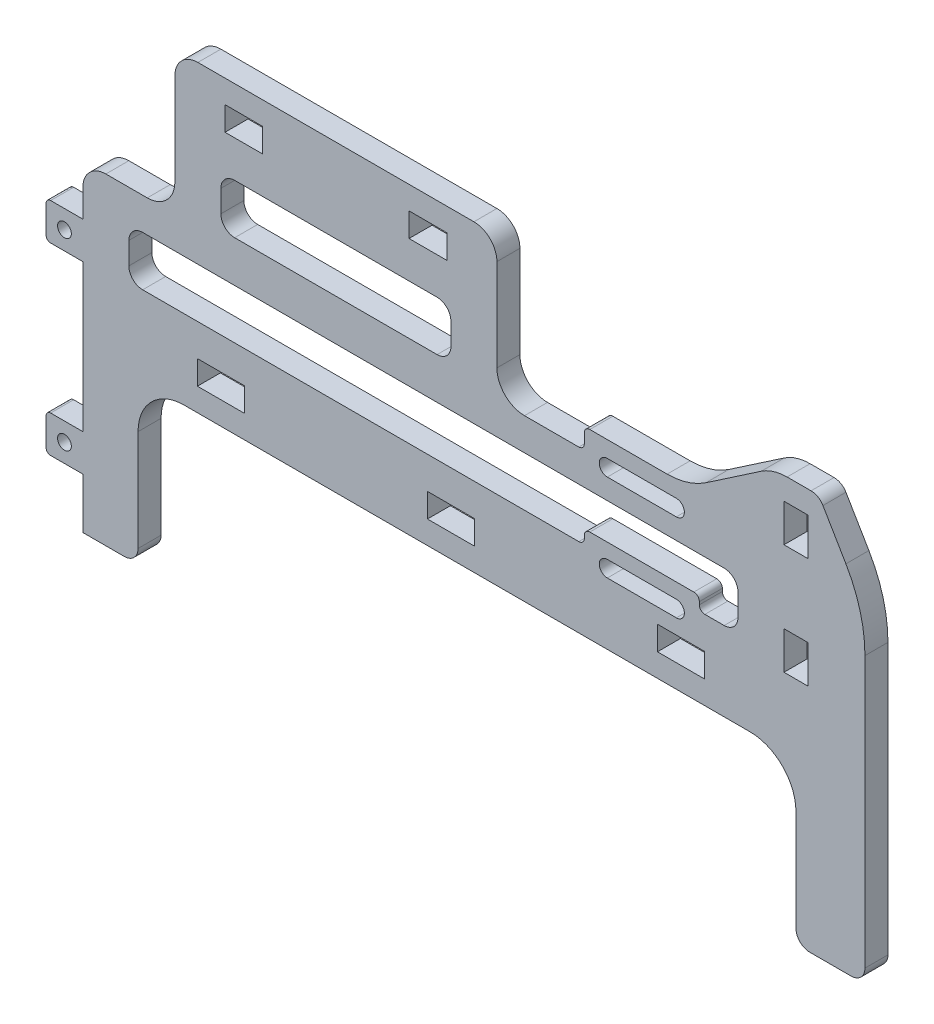
SolidWorks part; units mm, degrees
ref_plane "Alzado" through (0, 0, 0) normal (0, 0, 1) x (1, 0, 0)
ref_plane "Planta" through (0, 0, 0) normal (0, 1, 0) x (1, 0, 0)
ref_plane "Vista lateral" through (0, 0, 0) normal (1, 0, 0) x (0, 0, -1)
sketch "Croquis1" plane through (0, 0, 0) normal (0, 0, 1) x (1, 0, 0)
  line L0 (0, 0) -> (0, 70)
  line L1 (0, 70) -> (125, 70)
  line L2 (125, 70) -> (150, 87)
  line L3 (150, 87) -> (160, 87)
  line L4 (160, 87) -> (170, 70)
  line L5 (170, 70) -> (170, 0)
  line L6 (170, 0) -> (0, 0)
  dimension "D1" = 17
  dimension "D2" = 70
  dimension "D3" = 125
  dimension "D4" = 10
  dimension "D5" = 10
  dimension "D6" = 25
extrude "Saliente-Extruir1" add sketch "Croquis1" along normal blind 5
sketch "Croquis2" plane through (0, 0, 5) normal (0, 0, 1) x (1, 0, 0)
  line L0 (0, 0) -> (170, 0) construction
  line L1 (12, 0) -> (155, 0)
  line L2 (12, 0) -> (12, 35)
  line L3 (12, 35) -> (155, 35)
  line L4 (155, 0) -> (155, 35)
  line L5 (170, 0) -> (170, 70) construction
  line L6 (0, 70) -> (0, 0) construction
  dimension "D1" = 15
  dimension "D2" = 35
  dimension "D3" = 12
extrude "Cortar-Extruir1" cut sketch "Croquis2" against normal blind 5
fillet "Redondeo1" radius 10 2 edges at (155, 35, 2.5) (12, 35, 2.5)
sketch "Croquis3" plane through (0, 0, 0) normal (-1, 0, 0) x (0, 0, 1)
  line L0 (5, 70) -> (5, 0) construction
  line L1 (5, 11) -> (0, 11)
  line L2 (5, 11) -> (5, 19)
  line L3 (5, 19) -> (0, 19)
  line L4 (0, 11) -> (0, 19)
  line L5 (0, 70) -> (0, 0) construction
  line L6 (5, 0) -> (0, 0) construction
  line L7 (5, 59) -> (0, 59)
  line L8 (5, 59) -> (5, 51)
  line L9 (5, 51) -> (0, 51)
  line L10 (0, 59) -> (0, 51)
  point P12 (5, 15)
  point P16 (5, 55)
  dimension "D1" = 8
  dimension "D2" = 8
  dimension "D3" = 15
  dimension "D4" = 55
extrude "Saliente-Extruir2" add sketch "Croquis3" along normal blind 8
fillet "Redondeo2" radius 30 2 edges at (125, 70, 2.5) (170, 70, 2.5)
fillet "Redondeo3" radius 3 3 edges at (155, 0, 2.5) (12, 0, 2.5) (170, 0, 2.5)
sketch "Croquis4" plane through (0, 0, 5) normal (0, 0, 1) x (1, 0, 0)
  line L0 (160, 87) -> (150, 87) construction
  line L1 (152.4, 82.1) -> (157.6, 82.1)
  line L2 (152.4, 82.1) -> (152.4, 73.9)
  line L3 (152.4, 73.9) -> (157.6, 73.9)
  line L4 (157.6, 82.1) -> (157.6, 73.9)
  line L5 (152.4, 58.1) -> (157.6, 58.1)
  line L6 (152.4, 58.1) -> (152.4, 49.9)
  line L7 (152.4, 49.9) -> (157.6, 49.9)
  line L8 (157.6, 58.1) -> (157.6, 49.9)
  line L9 (0, 70) -> (0, 59) construction
  point P9 (152.4, 78)
  point P10 (152.4, 54)
  point P13 (155, 82.1)
  dimension "D1" = 5.2
  dimension "D2" = 8.2
  dimension "D3" = 5.2
  dimension "D4" = 8.2
  dimension "D5" = 24
  dimension "D6" = 4.9
  dimension "D7" = 155
extrude "Cortar-Extruir2" cut sketch "Croquis4" against normal through all
fillet "Redondeo4" radius 3 1 edges at (160, 87, 2.5)
fillet "Redondeo5" radius 10 1 edges at (150, 87, 2.5)
fillet "Redondeo6" radius 1 4 edges at (-8, 11, 2.5) (-8, 19, 2.5) (-8, 51, 2.5) (-8, 59, 2.5)
sketch "Croquis5" plane through (0, 0, 5) normal (0, 0, 1) x (1, 0, 0)
  line L0 (-8, 52) -> (-8, 58) construction
  line L1 (-8, 12) -> (-8, 18) construction
  circle A0 centre (-4, 55) radius 1.5
  circle A1 centre (-4, 15) radius 1.5
  point P7 (-8, 55)
  point P12 (-8, 15)
  dimension "D1" = 3
  dimension "D2" = 4
extrude "Cortar-Extruir3" cut sketch "Croquis5" against normal blind 5
sketch "Croquis6" plane through (0, 0, 5) normal (0, 0, 1) x (1, 0, 0)
  line L0 (74.9, 45.2) -> (85.1, 45.2)
  line L1 (24.9, 45.2) -> (35.1, 45.2)
  line L2 (24.9, 45.2) -> (24.9, 40)
  line L3 (24.9, 40) -> (35.1, 40)
  line L4 (35.1, 45.2) -> (35.1, 40)
  line L5 (74.9, 45.2) -> (74.9, 40)
  line L6 (74.9, 40) -> (85.1, 40)
  line L7 (85.1, 45.2) -> (85.1, 40)
  line L8 (124.9, 45.2) -> (135.1, 45.2)
  line L9 (124.9, 45.2) -> (124.9, 40)
  line L10 (124.9, 40) -> (135.1, 40)
  line L11 (135.1, 45.2) -> (135.1, 40)
  line L12 (145, 35) -> (22, 35) construction
  line L13 (0, 51) -> (0, 19) construction
  point P14 (30, 40)
  point P15 (80, 40)
  point P16 (130, 40)
  dimension "D1" = 5.2
  dimension "D2" = 10.2
  dimension "D3" = 5.2
  dimension "D4" = 10.2
  dimension "D5" = 5.2
  dimension "D6" = 10.2
  dimension "D7" = 50
  dimension "D8" = 50
  dimension "D9" = 5
  dimension "D10" = 30
extrude "Cortar-Extruir4" cut sketch "Croquis6" against normal blind 5
sketch "Croquis7" plane through (0, 0, 5) normal (0, 0, 1) x (1, 0, 0)
  line L0 (0, 70) -> (0, 59) construction
  line L1 (10, 63) -> (142.4, 63)
  line L2 (10, 63) -> (10, 52.2)
  line L3 (10, 52.2) -> (142.4, 52.2)
  line L4 (142.4, 63) -> (142.4, 52.2)
  line L5 (115.7663, 70) -> (0, 70) construction
  line L6 (35.1, 45.2) -> (24.9, 45.2) construction
  line L7 (152.4, 58.1) -> (152.4, 49.9) construction
  dimension "D1" = 10
  dimension "D2" = 7
  dimension "D3" = 7
  dimension "D4" = 10
extrude "Cortar-Extruir5" cut sketch "Croquis7" against normal blind 5
sketch "Croquis8" plane through (0, 0, 5) normal (0, 0, 1) x (1, 0, 0)
  line L0 (115.7663, 70) -> (0, 70) construction
  line L1 (20, 70) -> (90, 70)
  line L2 (20, 70) -> (20, 101)
  line L3 (20, 101) -> (90, 101)
  line L4 (90, 70) -> (90, 101)
  line L5 (0, 70) -> (0, 59) construction
  dimension "D1" = 31
  dimension "D2" = 70
  dimension "D3" = 20
extrude "Saliente-Extruir3" add sketch "Croquis8" against normal blind 5
sketch "Croquis9" plane through (0, 0, 5) normal (0, 0, 1) x (1, 0, 0)
  line L0 (20, 101) -> (20, 70) construction
  line L1 (30.9, 96) -> (39.1, 96)
  line L2 (30.9, 96) -> (30.9, 90.8)
  line L3 (30.9, 90.8) -> (39.1, 90.8)
  line L4 (39.1, 96) -> (39.1, 90.8)
  line L5 (70.9, 96) -> (79.1, 96)
  line L6 (70.9, 96) -> (70.9, 90.8)
  line L7 (70.9, 90.8) -> (79.1, 90.8)
  line L8 (79.1, 96) -> (79.1, 90.8)
  line L9 (90, 70) -> (90, 101) construction
  line L10 (90, 101) -> (20, 101) construction
  point P8 (35, 96)
  point P11 (75, 96)
  point P16 (0, 0)
  dimension "D1" = 8.2
  dimension "D2" = 5.2
  dimension "D3" = 8.2
  dimension "D4" = 5.2
  dimension "D5" = 15
  dimension "D6" = 15
  dimension "D7" = 5
extrude "Cortar-Extruir6" cut sketch "Croquis9" against normal blind 5
sketch "Croquis10" plane through (0, 0, 5) normal (0, 0, 1) x (1, 0, 0)
  line L0 (20, 101) -> (20, 70) construction
  line L1 (30, 82.8) -> (80, 82.8)
  line L2 (30, 82.8) -> (30, 72)
  line L3 (30, 72) -> (80, 72)
  line L4 (80, 82.8) -> (80, 72)
  line L5 (30.9, 90.8) -> (39.1, 90.8) construction
  line L6 (142.4, 63) -> (10, 63) construction
  line L7 (90, 70) -> (90, 101) construction
  dimension "D1" = 10
  dimension "D2" = 8
  dimension "D3" = 9
  dimension "D4" = 10
extrude "Cortar-Extruir7" cut sketch "Croquis10" against normal blind 5
fillet "Redondeo9" radius 3 4 edges at (30, 72, 2.5) (80, 72, 2.5) (80, 82.8, 2.5) (30, 82.8, 2.5)
fillet "Redondeo10" radius 6 2 edges at (90, 70, 2.5) (20, 70, 2.5)
fillet "Redondeo11" radius 5 2 edges at (90, 101, 2.5) (20, 101, 2.5)
fillet "Redondeo12" radius 5 1 edges at (0, 70, 2.5)
sketch "Croquis12" plane through (0, 0, 5) normal (0, 0, 1) x (1, 0, 0)
  line L1 (109, 74.5) -> (131.5698, 74.5)
  line L2 (109, 74.5) -> (109, 63)
  line L3 (109, 52.2) -> (134, 52.2)
  line L4 (131.5698, 74.5) -> (131.5698, 63)
  line L5 (10, 52.2) -> (142.4, 52.2) construction
  line L7 (109, 63) -> (131.5698, 63)
  line L8 (142.4, 63) -> (10, 63) construction
  line L9 (109, 55.2) -> (134, 55.2)
  line L10 (109, 55.2) -> (109, 52.2)
  line L11 (134, 55.2) -> (134, 52.2)
  line L12 (142.4, 52.2) -> (142.4, 63) construction
  line L13 (115.7663, 70) -> (96, 70) construction
  arc A0 (115.7663, 70) -> (132.6356, 75.1922) centre (115.7663, 100) ccw construction
  point P5 (131.7518, 74.6137)
  point P16 (0, 0)
  point P17 (134.5707, 63)
  point P18 (0, 0)
  point P19 (131.3914, 74.3903)
  point P23 (132.6356, 75.1922)
  point P24 (0, 0)
  dimension "D1" = 4.5
  dimension "D2" = 8.4
  dimension "D3" = 3
  dimension "D4" = 25
extrude "Saliente-Extruir4" add sketch "Croquis12" against normal blind 5
sketch "Croquis11" plane through (0, 0, 5) normal (0, 0, 1) x (1, 0, 0)
  line L1 (129, 50.2) -> (114, 50.2) construction
  line L2 (129, 48.45) -> (114, 48.45)
  line L3 (129, 51.95) -> (114, 51.95)
  line L4 (0, 51) -> (0, 19) construction
  line L5 (135.1, 45.2) -> (124.9, 45.2) construction
  line L6 (129, 69.2) -> (114, 69.2) construction
  line L7 (129, 67.45) -> (114, 67.45)
  line L8 (129, 70.95) -> (114, 70.95)
  arc A1 (129, 48.45) -> (129, 51.95) centre (129, 50.2) ccw
  arc A2 (114, 51.95) -> (114, 48.45) centre (114, 50.2) ccw
  arc A3 (129, 67.45) -> (129, 70.95) centre (129, 69.2) ccw
  arc A4 (114, 70.95) -> (114, 67.45) centre (114, 69.2) ccw
  point P2 (121.5, 50.2)
  point P13 (121.5, 69.2)
  point P18 (0, 0)
  dimension "D1" = 129
  dimension "D2" = 15
  dimension "D3" = 1.75
  dimension "D6" = 1.75
  dimension "D4" = 5
  dimension "D5" = 15
  dimension "D7" = 19
extrude "Cortar-Extruir8" cut sketch "Croquis11" against normal blind 5
fillet "Redondeo8" radius 3 4 edges at (142.4, 52.2, 2.5) (142.4, 63, 2.5) (10, 52.2, 2.5) (10, 63, 2.5)
fillet "Redondeo13" radius 1.2 6 edges at (134, 52.2, 2.5) (134, 55.2, 2.5) (109, 55.2, 2.5) (109, 52.2, 2.5) (109, 70, 2.5) (109, 74.5, 2.5)
fillet "Redondeo14" radius 15 1 edges at (131.5698, 74.5, 2.5)
